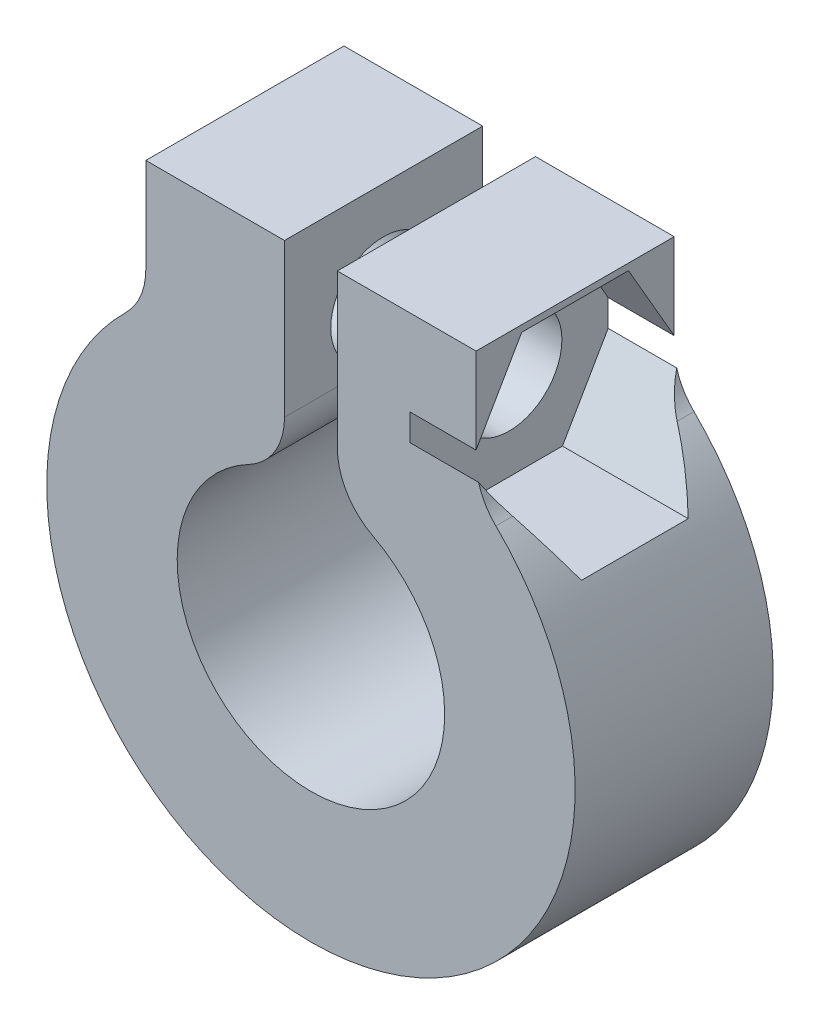
SolidWorks part; units mm, degrees
ref_plane "前视基准面" through (0, 0, 0) normal (0, 0, 1) x (1, 0, 0)
ref_plane "上视基准面" through (0, 0, 0) normal (0, 1, 0) x (1, 0, 0)
ref_plane "右视基准面" through (0, 0, 0) normal (1, 0, 0) x (0, 0, -1)
sketch "草图1" plane through (0, 0, 0) normal (0, 0, 1) x (1, 0, 0)
  line L0 (-5, 7.1414) -> (-5, 10)
  line L1 (-5, 10) -> (-0.8, 10)
  line L2 (5, 10) -> (5, 7.1414)
  line L3 (0, 0) -> (0, 10.0846) construction
  line L4 (-0.8, 10) -> (-0.8, 5.3631)
  line L5 (0.8, 10) -> (0.8, 5.3631)
  line L6 (0.8, 10) -> (5, 10)
  arc A0 (-1.8744, 3.5902) -> (1.8744, 3.5902) centre (0, 0) ccw
  arc A1 (5, 7.1414) -> (5.6, 5.7131) centre (7, 7.1414) ccw
  arc A2 (-5.6, 5.7131) -> (5.6, 5.7131) centre (0, 0) ccw
  arc A3 (-5, 7.1414) -> (-5.6, 5.7131) centre (-7, 7.1414) cw
  arc A4 (1.8744, 3.5902) -> (0.8, 5.3631) centre (2.8, 5.3631) cw
  arc A5 (-0.8, 5.3631) -> (-1.8744, 3.5902) centre (-2.8, 5.3631) cw
  dimension "D1" = 8.1
  dimension "D2" = 10
  dimension "D7" = 8
  dimension "D8" = 2
  dimension "D3" = 5
  dimension "D4" = 5
  dimension "D5" = 0.8
  dimension "D6" = 0.8
extrude "凸台-拉伸1" add sketch "草图1" along normal blind 6
sketch "草图2" plane through (-5, 0, 0) normal (-1, 0, 0) x (0, 0, 1)
  line L0 (6, 10) -> (0, 10) construction
  line L1 (0, 5.7131) -> (0, -8) construction
  circle A0 centre (3, 7) radius 1.6
  dimension "D2" = 3.2
  dimension "D1" = 3
  dimension "D3" = 3
extrude "切除-拉伸1" cut sketch "草图2" against normal through all and the other way through all
ref_plane "基准面1" through (-4, 0, 0) normal (-1, 0, 0) x (0, 0, 1)
sketch "草图3" plane through (-4, 0, 0) normal (-1, 0, 0) x (0, 0, 1)
  circle A0 centre (3, 7) radius 2.8
  dimension "D1" = 5.6
extrude "切除-拉伸2" cut sketch "草图3" along normal through all
ref_plane "基准面2" through (3, 0, 0) normal (1, 0, 0) x (0, 0, -1)
sketch "草图4" plane through (3, 0, 0) normal (1, 0, 0) x (0, 0, -1)
  line L1 (0.2332, 7) -> (-1.3834, 9.8)
  line L2 (-1.3834, 9.8) -> (-4.6166, 9.8)
  line L3 (-4.6166, 9.8) -> (-6.2332, 7)
  line L4 (-6.2332, 7) -> (-4.6166, 4.2)
  line L5 (-4.6166, 4.2) -> (-1.3834, 4.2)
  line L6 (-1.3834, 4.2) -> (0.2332, 7)
  circle A0 centre (-3, 7) radius 2.8 construction
  dimension "D1" = 5.6
extrude "切除-拉伸3" cut sketch "草图4" along normal through all
